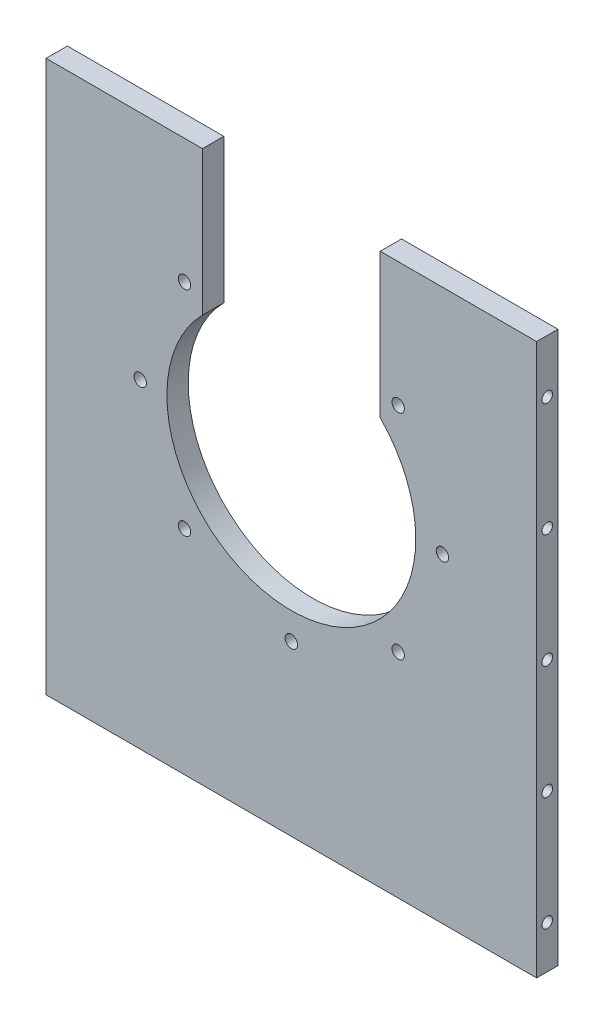
SolidWorks part; units mm, degrees
material "6061 合金"
ref_plane "前视基准面" through (0, 0, 0) normal (0, 0, 1) x (1, 0, 0)
ref_plane "上视基准面" through (0, 0, 0) normal (0, 1, 0) x (1, 0, 0)
ref_plane "右视基准面" through (0, 0, 0) normal (1, 0, 0) x (0, 0, -1)
other "Configuration Table"
sketch "草图1" plane through (0, 0, 0) normal (0, 0, 1) x (1, 0, 0)
  line L0 (-92.8514, 0) -> (171.3283, 0) construction
  line L5 (0, 149.9412) -> (0, -128.6129) construction
  line L7 (-69, 90) -> (69, 90)
  line L8 (-69, 90) -> (-69, -90)
  line L9 (-69, -90) -> (69, -90)
  line L10 (69, 90) -> (69, -90)
  circle A0 centre (0, 0) radius 42.5 construction
  circle A1 centre (0, 42.5) radius 1.75
  circle A14 centre (30.052, 30.052) radius 1.75
  circle A15 centre (42.5, 0) radius 1.75
  circle A16 centre (30.052, -30.052) radius 1.75
  circle A17 centre (0, -42.5) radius 1.75
  circle A18 centre (-30.052, -30.052) radius 1.75
  circle A19 centre (-42.5, 0) radius 1.75
  circle A20 centre (-30.052, 30.052) radius 1.75
  circle A21 centre (0, 0) radius 35
  point P25 (0, 0)
  point P29 (0, 0)
  point P31 (0, 0)
  dimension "D3" = 85
  dimension "D4" = 3.5
  dimension "D6" = 70
  dimension "D1" = 180
  dimension "D2" = 138
  dimension "D5" = 8
extrude "凸台-拉伸1" add sketch "草图1" along normal blind 6
sketch "草图2" plane through (0, 0, 0) normal (0, 0, -1) x (-1, 0, 0)
  line L0 (0, 0) -> (0, 93.8005) construction
  line L1 (-25, 70) -> (25, 70)
  line L2 (-25, 70) -> (-25, 20)
  line L3 (-25, 20) -> (25, 20)
  line L4 (25, 70) -> (25, 20)
  dimension "D1" = 20
  dimension "D2" = 50
  dimension "D3" = 50
extrude "切除-拉伸1" cut sketch "草图2" against normal blind 10 contours L1 L4 L3 L2
sketch "草图4" plane through (0, 0, 0) normal (0, 0, -1) x (-1, 0, 0)
  line L1 (-87.3385, 138.1682) -> (98.002, 138.1682)
  line L2 (-87.3385, 138.1682) -> (-87.3385, 65.052)
  line L3 (-87.3385, 65.052) -> (98.002, 65.052)
  line L4 (98.002, 138.1682) -> (98.002, 65.052)
  circle A0 centre (-30.052, 30.052) radius 1.75 construction
  dimension "D1" = 35
extrude "切除-拉伸3" cut sketch "草图4" against normal blind 10
ref_plane "基准面1" through (0, 0, 0) normal (-1, 0, 0) x (0, 0, 1)
sketch "草图3" plane through (-69, 0, 0) normal (-1, 0, 0) x (0, 0, 1)
  line L0 (3, 79.1888) -> (3, -83.996) construction
  line L1 (6, 65.052) -> (6, -90) construction
  line L2 (0, 65.052) -> (0, -90) construction
  line L3 (-24.8954, 0) -> (42.9436, 0) construction
  line L4 (6, 65.052) -> (0, 65.052) construction
  line L5 (3, 50.052) -> (3, 18.052) construction
  circle A0 centre (3, 50.052) radius 1.5
  circle A2 centre (3, 18.052) radius 1.5
  circle A3 centre (3, -13.948) radius 1.5
  circle A4 centre (3, -45.948) radius 1.5
  circle A5 centre (3, -77.948) radius 1.5
  circle A6 centre (3, -109.948) radius 1.5
  dimension "D1" = 3
  dimension "D2" = 15
  dimension "D3" = 6
  dimension "D4" = 32
extrude "切除-拉伸2" cut sketch "草图3" against normal blind 15
mirror "镜向1" about plane through (0, 0, 0) normal (-1, 0, 0) of "切除-拉伸2"
